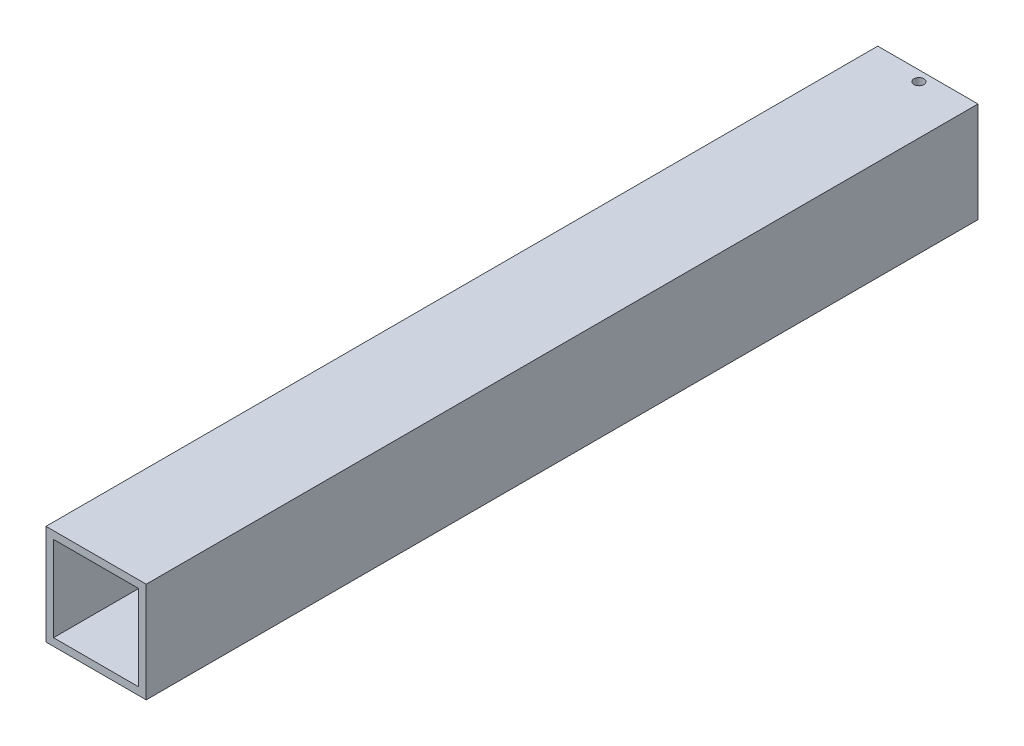
SolidWorks part; units mm, degrees
ref_plane "Płaszczyzna przednia" through (0, 0, 0) normal (0, 0, 1) x (1, 0, 0)
ref_plane "Płaszczyzna górna" through (0, 0, 0) normal (0, 1, 0) x (1, 0, 0)
ref_plane "Płaszczyzna prawa" through (0, 0, 0) normal (1, 0, 0) x (0, 0, -1)
sketch "Szkic1" plane through (0, 0, 0) normal (0, 0, 1) x (1, 0, 0)
  line L2 (-30.423, 18.5) -> (-30.423, -1.5)
  line L3 (-30.423, -1.5) -> (-10.423, -1.5)
  line L4 (-10.423, 18.5) -> (-10.423, -1.5)
  line L8 (-30.423, 18.5) -> (-10.423, 18.5)
  line L10 (-28.923, 17) -> (-11.923, 17)
  line L11 (-28.923, 17) -> (-28.923, 0)
  line L12 (-28.923, 0) -> (-11.923, 0)
  line L13 (-11.923, 17) -> (-11.923, 0)
  dimension "D1" = 20
  dimension "D2" = 20
  dimension "D3" = 1.5
  dimension "D4" = 1.5
  dimension "D5" = 1.5
  dimension "D6" = 1.5
extrude "Dodanie-wyciągnięcie1" add sketch "Szkic1" along normal up to surface (166 mm away)
sketch "Szkic3" plane through (0, 18.5, 0) normal (0, 1, 0) x (1, 0, 0)
  circle A0 centre (-20.1716, -2.0464) radius 1
extrude "Wytnij-wyciągnięcie1" cut sketch "Szkic3" against normal through all
